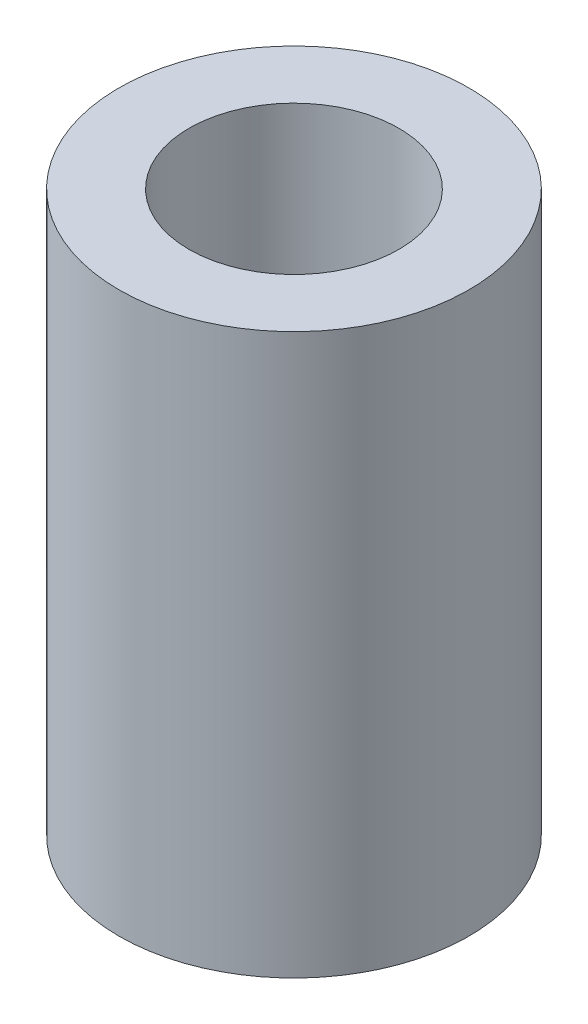
SolidWorks part; units mm, degrees
ref_plane "前视基准面" through (0, 0, 0) normal (0, 0, 1) x (1, 0, 0)
ref_plane "上视基准面" through (0, 0, 0) normal (0, 1, 0) x (1, 0, 0)
ref_plane "右视基准面" through (0, 0, 0) normal (1, 0, 0) x (0, 0, -1)
other "Configuration Table"
sketch "草图1" plane through (0, 0, 0) normal (0, 1, 0) x (1, 0, 0)
  circle A0 centre (0, 0) radius 1.5
  circle A1 centre (0, 0) radius 2.5
extrude "凸台-拉伸1" add sketch "草图1" along normal blind 8
